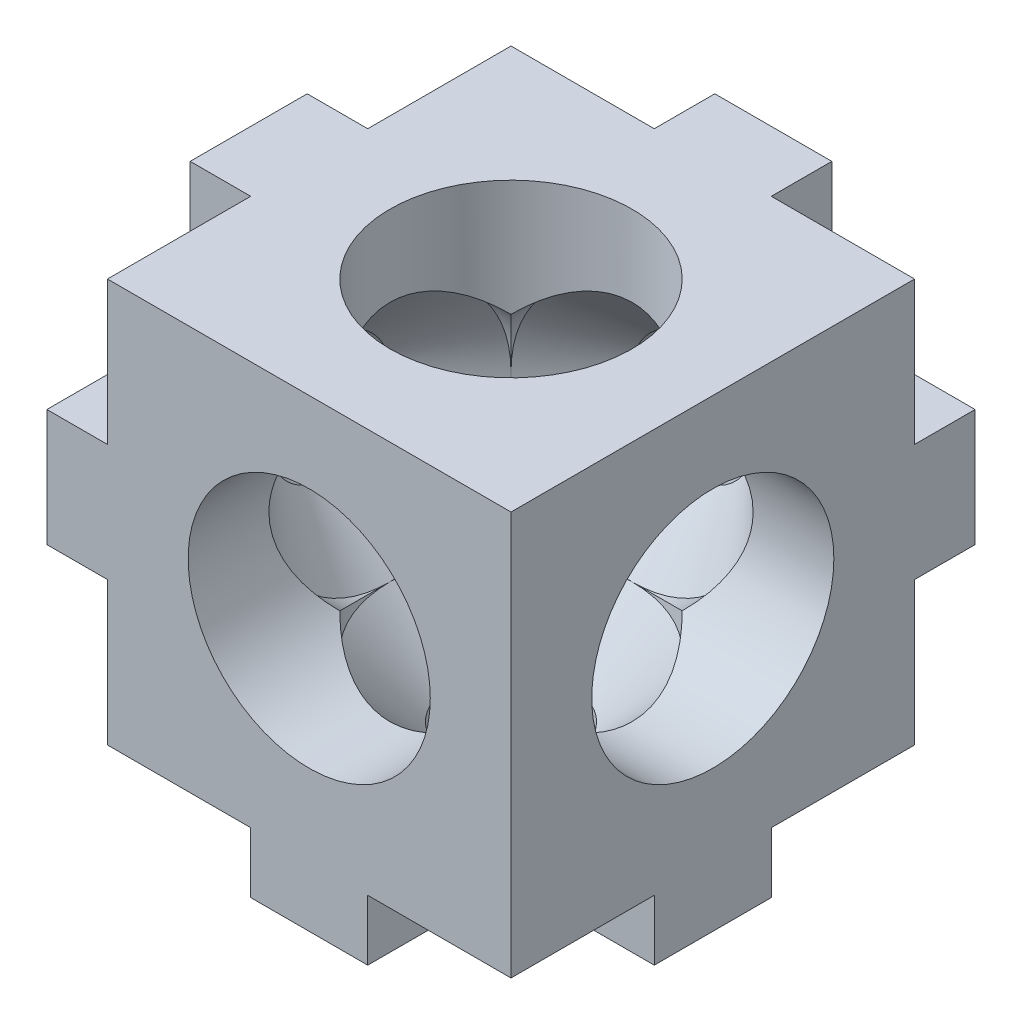
SolidWorks part; units mm, degrees
ref_plane "Front Plane" through (0, 0, 0) normal (0, 0, 1) x (1, 0, 0)
ref_plane "Top Plane" through (0, 0, 0) normal (0, 1, 0) x (1, 0, 0)
ref_plane "Right Plane" through (0, 0, 0) normal (1, 0, 0) x (0, 0, -1)
sketch "Sketch1" plane through (0, 0, 0) normal (0, 1, 0) x (1, 0, 0)
  line L1 (-10, 10) -> (10, 10)
  line L2 (-10, 10) -> (-10, -10)
  line L3 (-10, -10) -> (10, -10)
  line L4 (10, 10) -> (10, -10)
  line L5 (-10, 10) -> (10, -10) construction
  line L6 (-10, -10) -> (10, 10) construction
  point P0 (0, 0)
extrude "Boss-Extrude1" add sketch "Sketch1" against normal mid plane 20
sketch "Z" plane through (0, 0, 10) normal (0, 0, 1) x (1, 0, 0)
  circle A0 centre (0, 0) radius 6
sketch "Y" plane through (0, 10, 0) normal (0, 1, 0) x (1, 0, 0)
  circle A0 centre (0, 0) radius 6
sketch "X" plane through (10, 0, 0) normal (1, 0, 0) x (0, 0, -1)
  circle A0 centre (0, 0) radius 6
extrude "Cut-Extrude1" cut sketch "Z" against normal blind 16
extrude "Cut-Extrude2" cut sketch "Y" against normal blind 16
extrude "Cut-Extrude3" cut sketch "X" against normal blind 16
hole_wizard "CSK for M6 Flat Head Machine Screw23" positions "Sketch22" profile "Sketch23" countersink size "M6" standard "ANSI Metric" end condition through all
sketch "Sketch22" plane through (-6, 0, 0) normal (1, 0, 0) x (0, 0, -1)
  point P0 (0, 0)
sketch "Sketch23" plane through (-6, 0, 0) normal (0, 1, 0) x (0, 0, -1)
  line L0 (0, 0) -> (0, 4)
  line L1 (0, 4) -> (3, 4)
  line L2 (3, 4) -> (3, 3)
  line L3 (3, 3) -> (6, 0)
  line L5 (6, 0) -> (0, 0)
  line L6 (-3, 3) -> (-6, 0) construction
  line L11 (0, -6.35) -> (0, 107.95) construction
  dimension "Thru Hole Dia." = 6
  dimension "Thru Hole Depth" = 4
  dimension "Near C'Sink Dia." = 12
  dimension "Near C'Sink Angle" = 90
hole_wizard "CSK for M6 Flat Head Machine Screw24" positions "Sketch25" profile "Sketch24" countersink size "M6" standard "ANSI Metric" end condition through all
sketch "Sketch25" plane through (0, 0, -6) normal (0, 0, 1) x (1, 0, 0)
  point P0 (0, 0)
sketch "Sketch24" plane through (0, 0, -6) normal (1, 0, 0) x (0, -1, 0)
  line L0 (0, 0) -> (0, 4)
  line L1 (0, 4) -> (3, 4)
  line L2 (3, 4) -> (3, 3)
  line L3 (3, 3) -> (6, 0)
  line L5 (6, 0) -> (0, 0)
  line L6 (-3, 3) -> (-6, 0) construction
  line L11 (0, -6.35) -> (0, 107.95) construction
  dimension "Thru Hole Dia." = 6
  dimension "Thru Hole Depth" = 4
  dimension "Near C'Sink Dia." = 12
  dimension "Near C'Sink Angle" = 90
hole_wizard "CSK for M6 Flat Head Machine Screw25" positions "Sketch27" profile "Sketch26" countersink size "M6" standard "ANSI Metric" end condition through all
sketch "Sketch27" plane through (0, -6, 0) normal (0, 1, 0) x (1, 0, 0)
  point P0 (0, 0)
sketch "Sketch26" plane through (0, -6, 0) normal (1, 0, 0) x (0, 0, 1)
  line L0 (0, 0) -> (0, 4)
  line L1 (0, 4) -> (3, 4)
  line L2 (3, 4) -> (3, 3)
  line L3 (3, 3) -> (6, 0)
  line L5 (6, 0) -> (0, 0)
  line L6 (-3, 3) -> (-6, 0) construction
  line L11 (0, -6.35) -> (0, 107.95) construction
  dimension "Thru Hole Dia." = 6
  dimension "Thru Hole Depth" = 4
  dimension "Near C'Sink Dia." = 12
  dimension "Near C'Sink Angle" = 90
sketch "Sketch32" plane through (0, 0, 0) normal (0, 0, 1) x (1, 0, 0)
  line L0 (-10, -10) -> (-10, -4.6)
  line L1 (-13, -4.6) -> (-10, -4.6)
  line L2 (-13, -4.6) -> (-13, -11)
  line L3 (-11, -13) -> (-4.6, -13)
  line L4 (-4.6, -10) -> (-4.6, -13)
  line L5 (-13, -11) -> (-11, -13)
  line L7 (-10, -10) -> (-4.6, -10)
  line L8 (-10, -10) -> (10, -10) construction
  line L9 (-10, -10) -> (-10, 10) construction
  line L10 (10, -10) -> (4.6, -10)
  line L11 (10, -10) -> (10, -13)
  line L12 (10, -13) -> (4.6, -13)
  line L13 (4.6, -10) -> (4.6, -13)
  line L14 (-10, 10) -> (-13, 10)
  line L15 (-10, 10) -> (-10, 4.6)
  line L16 (-10, 4.6) -> (-13, 4.6)
  line L17 (-13, 10) -> (-13, 4.6)
  point P0 (-10, -10)
  dimension "D1" = 5.4
  dimension "D2" = 3
  dimension "D3" = 2.8284
extrude "con" add sketch "Sketch32" along normal mid plane 5.8
sketch "AX" plane through (0, 0, 0) normal (0, 0, 1) x (1, 0, 0)
  line L0 (-1000, 0) -> (49000, 0) construction
sketch "AY" plane through (0, 0, 0) normal (0, 0, 1) x (1, 0, 0)
  line L0 (0, -1000) -> (0, 49000) construction
sketch "AZ" plane through (0, 0, 0) normal (1, 0, 0) x (0, 0, -1)
  line L0 (-1000, 0) -> (49000, 0) construction
pattern_circular "CirPattern5" count 2 every 270 about axis through (0, 0, 0) along (0, 1, 0) of "con"
pattern_circular "CirPattern9" count 2 every 90 about axis through (0, 0, 0) along (1, 0, 0) of "con"
